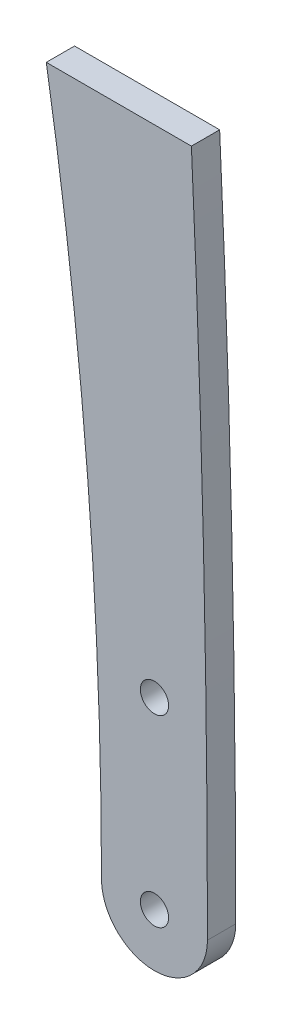
SolidWorks part; units mm, degrees
ref_plane "Front Plane" through (0, 0, 0) normal (0, 0, 1) x (1, 0, 0)
ref_plane "Top Plane" through (0, 0, 0) normal (0, 1, 0) x (1, 0, 0)
ref_plane "Right Plane" through (0, 0, 0) normal (1, 0, 0) x (0, 0, -1)
sketch "Sketch3" plane through (0, 0, 0) normal (0, 0, 1) x (1, 0, 0)
  line L0 (0, -43.3147) -> (0, 73.3108) construction
  line L1 (-76.0143, 73.3108) -> (78.3959, 73.3108) construction
  line L2 (-11.6675, 73.3108) -> (3.9838, 73.3108)
  arc A0 (-5.715, 0) -> (5.715, 0) centre (0, 0) ccw
  arc A1 (-5.715, 0) -> (-11.6675, 73.3108) centre (-460.1371, 0) ccw
  arc A2 (5.715, 0) -> (3.9838, 73.3108) centre (-1547.3778, 0) ccw
  dimension "D1" = 11.43
extrude "Leg" add sketch "Sketch3" along normal blind 3.048
ref_plane "LegPlane" through (0, 0, 3.048) normal (0, 0, 1) x (1, 0, 0)
sketch "Sketch4" plane through (0, 0, 3.048) normal (0, 0, 1) x (1, 0, 0)
  line L0 (-14.8285, 0) -> (18.0569, 0) construction
  line L1 (0, 43.9274) -> (0, -20.1228) construction
  line L2 (-5.0149, 1.524) -> (4.1864, 1.524) construction
  line L3 (-3.6641, 18.288) -> (3.3368, 18.288) construction
  line L4 (-3.6641, 19.812) -> (3.3368, 19.812) construction
  circle A0 centre (0, 0) radius 1.524
  circle A1 centre (0, 19.812) radius 1.524
  dimension "D1" = 3.048
  dimension "D2" = 3.048
  dimension "D3" = 16.764
  dimension "D4" = 1.524
extrude "FeetHoles" cut sketch "Sketch4" against normal blind 3.048
sketch "Sketch5" plane through (0, 0, 3.048) normal (0, 0, 1) x (1, 0, 0)
  line L0 (-9.7247, -5.715) -> (9.6491, -5.715) construction
  line L1 (-9.7247, 0) -> (9.6491, 0) construction
  line L2 (0, 21.336) -> (0, -8.3893) construction
  line L3 (0, 19.812) -> (-9.7247, 19.812) construction
  line L4 (0, 19.812) -> (13.9575, 19.812) construction
  line L5 (0, 21.336) -> (12.202, 21.336) construction
  line L6 (0, -1.524) -> (13.9575, -1.524) construction
  circle A2 centre (0, 19.812) radius 1.524 construction
  circle A4 centre (0, 0) radius 1.524 construction
  dimension "D1" = 5.715
  dimension "D2" = 25.527
